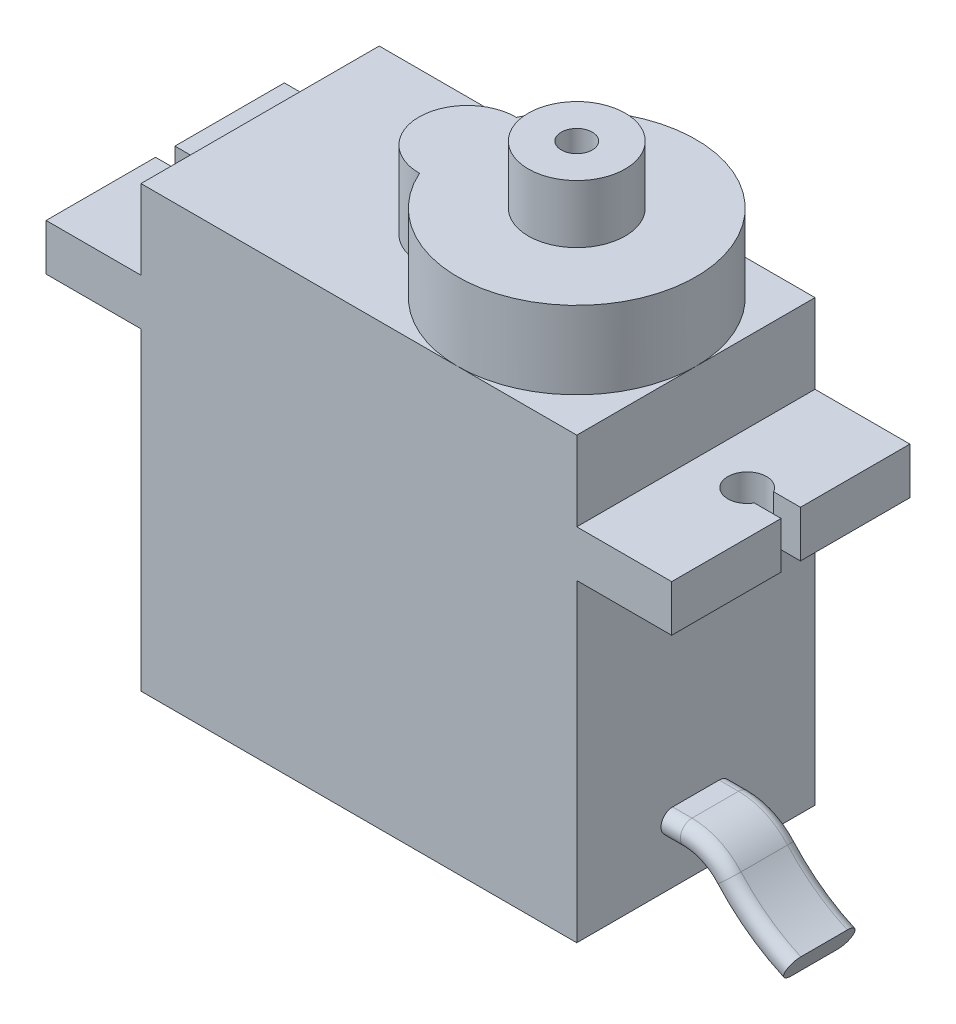
SolidWorks part; units mm, degrees
ref_plane "Front Plane" through (0, 0, 0) normal (0, 0, 1) x (1, 0, 0)
ref_plane "Top Plane" through (0, 0, 0) normal (0, 1, 0) x (1, 0, 0)
ref_plane "Right Plane" through (0, 0, 0) normal (1, 0, 0) x (0, 0, -1)
sketch "Sketch1" plane through (0, 0, 0) normal (0, 1, 0) x (1, 0, 0)
  circle A0 centre (0, 0) radius 6.15
  dimension "D1" = 12.3
extrude "Boss-Extrude1" add sketch "Sketch1" along normal blind 4
sketch "Sketch2" plane through (0, 0, 0) normal (0, 1, 0) x (1, 0, 0)
  line L1 (6.15, 6.15) -> (-16.35, 6.15)
  line L2 (6.15, 6.15) -> (6.15, -6.15)
  line L3 (6.15, -6.15) -> (-16.35, -6.15)
  line L4 (-16.35, 6.15) -> (-16.35, -6.15)
  circle A0 centre (0, 0) radius 6.15 construction
  dimension "D1" = 22.5
extrude "Boss-Extrude2" add sketch "Sketch2" against normal blind 4.1
sketch "Sketch3" plane through (0, -4.1, 0) normal (0, -1, 0) x (1, 0, 0)
  line L0 (-5.1, 6.15) -> (-5.1, -6.15) construction
  line L1 (-16.35, 6.15) -> (6.15, 6.15) construction
  line L2 (6.15, -6.15) -> (-16.35, -6.15) construction
  line L3 (-21.25, 6.15) -> (11.05, 6.15)
  line L4 (11.05, 6.15) -> (11.05, 0.5)
  line L5 (11.05, 0.5) -> (9.666, 0.5)
  line L6 (-21.25, -0.5) -> (-21.25, -6.15)
  line L7 (9.666, -0.5) -> (11.05, -0.5)
  line L8 (11.05, -0.5) -> (11.05, -6.15)
  line L9 (11.05, -6.15) -> (-21.25, -6.15)
  line L10 (-19.866, -0.5) -> (-21.25, -0.5)
  line L11 (-21.25, 0.5) -> (-19.866, 0.5)
  line L12 (-21.25, 6.15) -> (-21.25, 0.5)
  line L13 (7.8, 0) -> (-18, 0) construction
  arc A0 (9.666, 0.5) -> (9.666, -0.5) centre (8.8, 0) ccw
  arc A1 (-19.866, 0.5) -> (-19.866, -0.5) centre (-19, 0) cw
  dimension "D2" = 1
  dimension "D1" = 1
  dimension "D3" = 16.15
  dimension "D4" = 25.8
extrude "Boss-Extrude3" add sketch "Sketch3" along normal blind 2.4
sketch "Sketch4" plane through (0, -6.5, 0) normal (0, -1, 0) x (1, 0, 0)
  line L1 (-16.35, 6.15) -> (6.15, 6.15)
  line L2 (-16.35, 6.15) -> (-16.35, -6.15)
  line L3 (-16.35, -6.15) -> (6.15, -6.15)
  line L4 (6.15, 6.15) -> (6.15, -6.15)
extrude "Boss-Extrude4" add sketch "Sketch4" along normal blind 23
sketch "Sketch5" plane through (0, 0, 6.15) normal (0, 0, 1) x (1, 0, 0)
  line L0 (14.2082, -22.7) -> (-24.6614, -22.7)
  line L1 (-16.35, 0) -> (0, 0) construction
  dimension "D1" = 22.7
extrude "Cut-Extrude1" cut sketch "Sketch5" against normal through all and the other way through all
sketch "Sketch6" plane through (0, 4, 0) normal (0, 1, 0) x (1, 0, 0)
  line L0 (-8.15, 0) -> (6.15, 0) construction
  circle A0 centre (-5.65, 0) radius 2.5
  circle A1 centre (0, 0) radius 6.15 construction
  dimension "D1" = 5
  dimension "D2" = 14.3
extrude "Boss-Extrude5" add sketch "Sketch6" against normal blind 23
sketch "Sketch7" plane through (0, 4, 0) normal (0, 1, 0) x (1, 0, 0)
  circle A0 centre (0, 0) radius 2.5
  circle A1 centre (0, 0) radius 0.8
  dimension "D1" = 1.6
  dimension "D2" = 5
extrude "Boss-Extrude6" add sketch "Sketch7" along normal blind 3
sketch "Sketch8" plane through (6.15, 0, 0) normal (1, 0, 0) x (0, 0, -1)
  line L0 (-1.2, -19.7) -> (1.2, -19.7) construction
  line L1 (-1.2, -19.1) -> (1.2, -19.1)
  line L2 (-1.2, -20.3) -> (1.2, -20.3)
  line L3 (6.15, -22.7) -> (-6.15, -22.7) construction
  arc A0 (-1.2, -19.1) -> (-1.2, -20.3) centre (-1.2, -19.7) ccw
  arc A1 (1.2, -20.3) -> (1.2, -19.1) centre (1.2, -19.7) ccw
  point P2 (0, -19.7)
  point P9 (0, -22.7)
  dimension "D1" = 1.2
  dimension "D2" = 2.4
  dimension "D3" = 3.6
sketch "Sketch9" plane through (0, 0, 0) normal (0, 0, 1) x (1, 0, 0)
  line L0 (6.15, -19.7) -> (7.1491, -19.7)
  arc A0 (7.1491, -19.7) -> (9.234, -20.6359) centre (7.1491, -22.4903) cw
  arc A1 (9.234, -20.6359) -> (12.5277, -23.0382) centre (16.4157, -14.2484) ccw
sweep "Sweep1" add profiles "Sketch8" path "Sketch9"
scale "Scale1" scale about centroid uniform scaling yes scale factor 2
